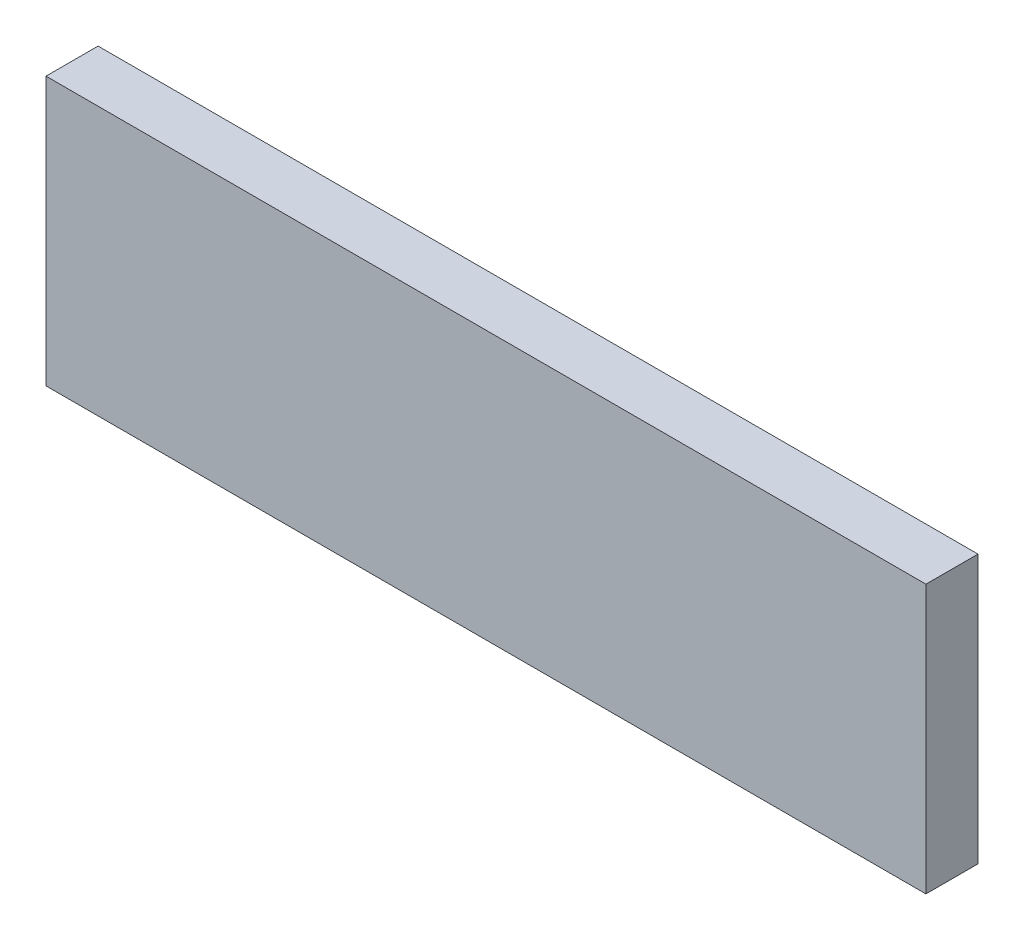
SolidWorks part; units mm, degrees
ref_plane "Front Plane" through (0, 0, 0) normal (0, 0, 1) x (1, 0, 0)
ref_plane "Top Plane" through (0, 0, 0) normal (0, 1, 0) x (1, 0, 0)
ref_plane "Right Plane" through (0, 0, 0) normal (1, 0, 0) x (0, 0, -1)
sketch "Sketch1" plane through (0, 0, 0) normal (0, 0, 1) x (1, 0, 0)
  line L1 (22.3843, -5.4594) -> (-20.5358, -5.4594)
  line L2 (22.3843, -5.4594) -> (22.3843, -18.5448)
  line L3 (22.3843, -18.5448) -> (-20.5358, -18.5448)
  line L4 (-20.5358, -5.4594) -> (-20.5358, -18.5448)
extrude "Boss-Extrude1" add sketch "Sketch1" along normal blind 2.54
